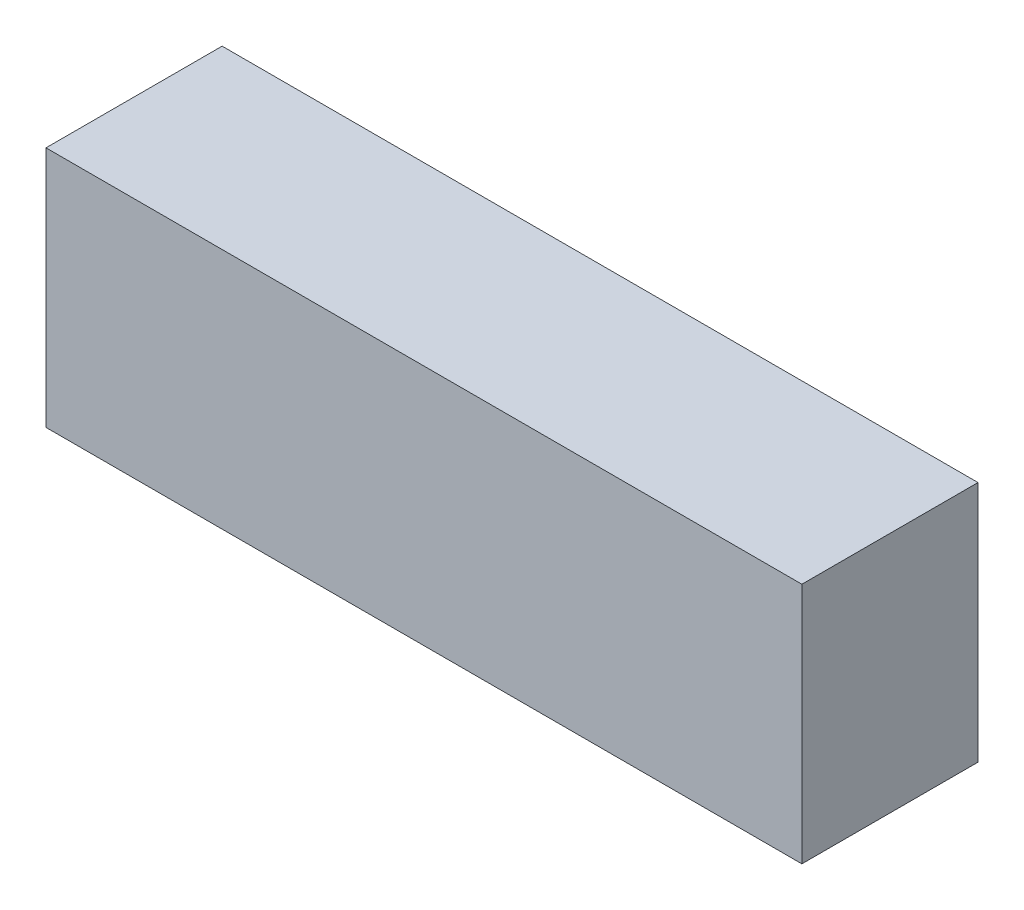
SolidWorks part; units mm, degrees
ref_plane "Front Plane" through (0, 0, 0) normal (0, 0, 1) x (1, 0, 0)
ref_plane "Top Plane" through (0, 0, 0) normal (0, 1, 0) x (1, 0, 0)
ref_plane "Right Plane" through (0, 0, 0) normal (1, 0, 0) x (0, 0, -1)
sketch "Sketch1" plane through (0, 0, 0) normal (0, 0, 1) x (1, 0, 0)
  line L1 (40.379, 20.537) -> (-62.621, 20.537)
  line L2 (40.379, 20.537) -> (40.379, 53.537)
  line L3 (40.379, 53.537) -> (-62.621, 53.537)
  line L4 (-62.621, 20.537) -> (-62.621, 53.537)
  line L5 (40.379, 20.537) -> (-62.621, 53.537) construction
  line L6 (40.379, 53.537) -> (-62.621, 20.537) construction
  point P0 (-11.121, 37.037)
  dimension "D1" = 33
  dimension "D2" = 103
extrude "Boss-Extrude1" add sketch "Sketch1" along normal blind 24
